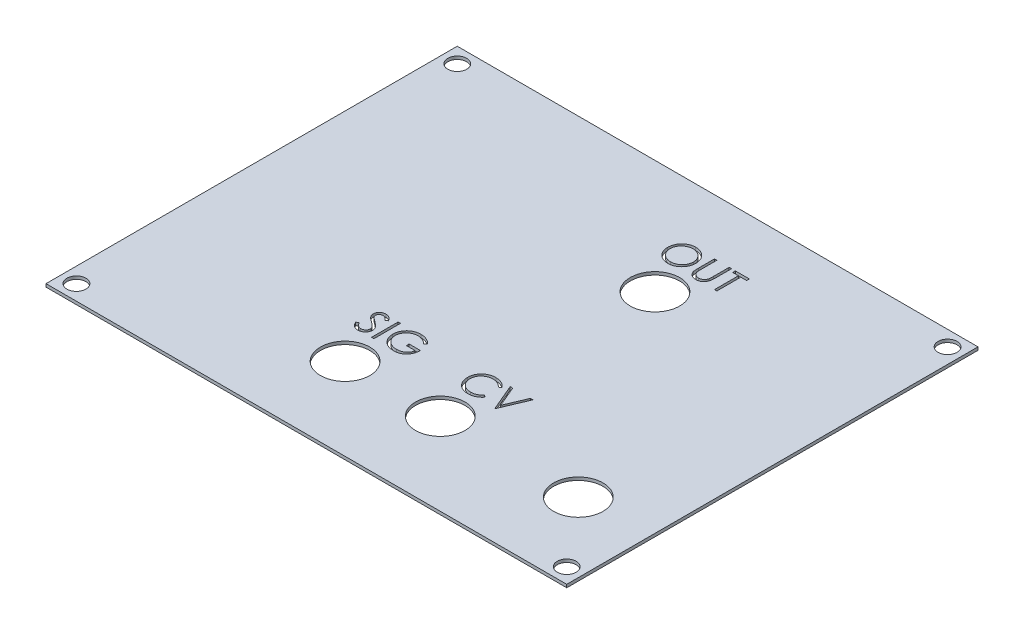
SolidWorks part; units mm, degrees
ref_plane "Front Plane" through (0, 0, 0) normal (0, 0, 1) x (1, 0, 0)
ref_plane "Top Plane" through (0, 0, 0) normal (0, 1, 0) x (1, 0, 0)
ref_plane "Right Plane" through (0, 0, 0) normal (1, 0, 0) x (0, 0, -1)
sketch "Sketch1" plane through (0, 0, 0) normal (0, 1, 0) x (1, 0, 0)
  line L12 (0, 50.1) -> (64.5, 50.1) construction
  line L17 (0, 50.1) -> (0, 0) construction
  line L18 (0, 0) -> (64.5, 0) construction
  line L19 (64.5, 50.1) -> (64.5, 0) construction
  line L20 (26.516, 14.279) -> (26.516, 3.379) construction
  line L21 (21.616, 3.379) -> (31.416, 3.379) construction
  line L22 (21.616, 3.379) -> (21.616, 14.279) construction
  line L23 (21.616, 14.279) -> (31.416, 14.279) construction
  line L24 (31.416, 3.379) -> (31.416, 14.279) construction
  line L25 (39.036, 14.279) -> (39.036, 3.379) construction
  line L26 (34.136, 3.379) -> (43.936, 3.379) construction
  line L27 (34.136, 3.379) -> (34.136, 14.279) construction
  line L28 (34.136, 14.279) -> (43.936, 14.279) construction
  line L29 (43.936, 3.379) -> (43.936, 14.279) construction
  line L30 (57.33, 14.44) -> (57.33, 2.94) construction
  line L31 (52.33, 2.94) -> (62.33, 2.94) construction
  line L32 (52.33, 2.94) -> (52.33, 14.44) construction
  line L33 (52.33, 14.44) -> (62.33, 14.44) construction
  line L34 (62.33, 2.94) -> (62.33, 14.44) construction
  line L35 (38.979, 42.577) -> (38.979, 31.677) construction
  line L36 (34.079, 42.577) -> (43.879, 42.577) construction
  line L37 (34.079, 42.577) -> (34.079, 31.677) construction
  line L38 (34.079, 31.677) -> (43.879, 31.677) construction
  line L39 (43.879, 42.577) -> (43.879, 31.677) construction
  line L46 (-2, 52.1) -> (66.5, 52.1)
  line L47 (-2, 52.1) -> (-2, -2)
  line L48 (-2, -2) -> (66.5, -2)
  line L49 (66.5, 52.1) -> (66.5, -2)
  circle A0 centre (0, 0) radius 1.25
  circle A1 centre (0, 50.1) radius 1.25
  circle A2 centre (64.5, 50.1) radius 1.25
  circle A3 centre (64.5, 0) radius 1.25
  circle A4 centre (26.516, 8.829) radius 3.25
  circle A5 centre (39.036, 8.829) radius 3.25
  circle A6 centre (57.33, 8.69) radius 3.25
  circle A7 centre (38.979, 37.127) radius 3.25
  dimension "D1" = 2.5
  dimension "D2" = 2.5
  dimension "D3" = 50.1
  dimension "D4" = 64.5
  dimension "D5" = 2.5
  dimension "D6" = 2.5
  dimension "D11" = 6.5
  dimension "D16" = 6.5
  dimension "D21" = 6.5
  dimension "D26" = 6.5
  dimension "D32" = 2
  dimension "D33" = 2
  dimension "D7" = 10.9
  dimension "D8" = 9.8
  dimension "D9" = 3.379
  dimension "D10" = 21.616
  dimension "D12" = 9.8
  dimension "D13" = 10.9
  dimension "D14" = 3.379
  dimension "D15" = 2.72
  dimension "D17" = 10
  dimension "D18" = 11.5
  dimension "D19" = 2.17
  dimension "D20" = 2.94
  dimension "D22" = 10.9
  dimension "D23" = 9.8
  dimension "D24" = 20.621
  dimension "D25" = 7.523
  dimension "D34" = 2
  dimension "D35" = 2
extrude "Boss-Extrude1" add sketch "Sketch1" along normal blind 0.4
sketch "Sketch2" plane through (0, 0.4, 0) normal (0, 1, 0) x (1, 0, 0)
  text T0 "SIG"
  text T1 "CV\r\n"
  text T2 "OUT"
extrude "Cut-Extrude1" cut sketch "Sketch2" against normal blind 0.4
